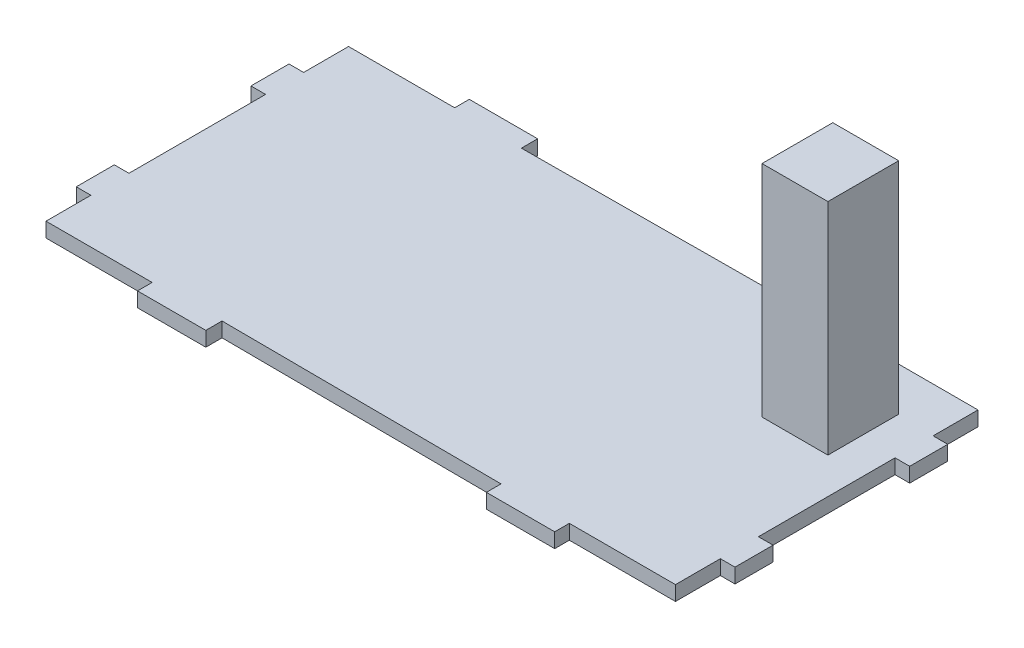
SolidWorks part; units mm, degrees
ref_plane "Front Plane" through (0, 0, 0) normal (0, 0, 1) x (1, 0, 0)
ref_plane "Top Plane" through (0, 0, 0) normal (0, 1, 0) x (1, 0, 0)
ref_plane "Right Plane" through (0, 0, 0) normal (1, 0, 0) x (0, 0, -1)
sketch "Sketch1" plane through (0, 0, 0) normal (0, 1, 0) x (1, 0, 0)
  line L1 (-67.5, 34) -> (67.5, 34)
  line L2 (-67.5, 34) -> (-67.5, -34)
  line L3 (-67.5, -34) -> (67.5, -34)
  line L4 (67.5, 34) -> (67.5, -34)
  line L5 (-67.5, 34) -> (67.5, -34) construction
  line L6 (-67.5, -34) -> (67.5, 34) construction
  point P0 (0, 0)
  dimension "D1" = 68
  dimension "D2" = 135
extrude "Boss-Extrude1" add sketch "Sketch1" along normal blind 3
sketch "Sketch2" plane through (0, 3, 0) normal (0, 1, 0) x (1, 0, 0)
  line L0 (-67.5, 34) -> (-64.5, 34)
  line L1 (67.5, 34) -> (-67.5, 34) construction
  line L2 (-64.5, 34) -> (-64.5, 21.8)
  line L3 (-64.5, 21.8) -> (-67.5, 21.8)
  line L4 (-67.5, 34) -> (-67.5, -34) construction
  line L5 (-67.5, 21.8) -> (-67.5, 14)
  line L6 (-67.5, 14) -> (-64.5, 14)
  line L7 (-64.5, 14) -> (-64.5, -14)
  line L8 (-64.5, -14) -> (-67.5, -14)
  line L9 (-67.5, -14) -> (-67.5, -21.8)
  line L10 (-67.5, -21.8) -> (-64.5, -21.8)
  line L11 (-64.5, -21.8) -> (-64.5, -34)
  line L12 (-67.5, -34) -> (67.5, -34) construction
  line L13 (-64.5, -34) -> (-67.5, -34)
  line L14 (-67.5, -34) -> (-67.5, -21.8)
  line L15 (-67.5, -14) -> (-67.5, 14)
  line L16 (-67.5, 21.8) -> (-67.5, 34)
  line M2 (67.5, 34) -> (-67.5, 34)
  line M3 (-67.5, 34) -> (-67.5, -34)
  line M4 (-67.5, -34) -> (67.5, -34)
  dimension "D1" = 3
  dimension "D2" = 12.2
  dimension "D3" = 7.8
  dimension "D4" = 28
  dimension "D5" = 7.8
  dimension "D6" = 12.2
extrude "Cut-Extrude1" cut sketch "Sketch2" against normal blind 3 contours L3 L2 M2 M3 | L8 L7 L6 M3 | L11 L10 M3 M4
mirror "Mirror1" about plane through (0, 0, 0) normal (1, 0, 0) of "Cut-Extrude1"
sketch "Sketch3" plane through (0, 3, 0) normal (0, 1, 0) x (1, 0, 0)
  line L0 (-64.5, 34) -> (-64.5, 31)
  line L1 (-64.5, 34) -> (-64.5, 21.8) construction
  line L2 (-64.5, 31) -> (-42.75, 31)
  line L3 (-42.75, 31) -> (-42.75, 34)
  line L4 (64.5, 34) -> (-64.5, 34) construction
  line L5 (-42.75, 34) -> (-28.75, 34)
  line L6 (-28.75, 34) -> (-28.75, 30.6714)
  line L7 (64.5, 34) -> (64.5, 31)
  line L8 (64.5, 34) -> (64.5, 21.8) construction
  line L9 (64.5, 31) -> (42.75, 31)
  line L10 (42.75, 31) -> (42.75, 34)
  line L11 (42.75, 34) -> (28.75, 34)
  line L12 (28.75, 34) -> (28.75, 31)
  line L13 (28.75, 31) -> (-28.75, 30.6714)
  line L14 (-64.5, 34) -> (-42.75, 34)
  line L15 (-28.75, 34) -> (28.75, 34)
  line L16 (42.75, 34) -> (64.5, 34)
  line M2 (64.5, 21.8) -> (64.5, 34)
  line M3 (64.5, 34) -> (-64.5, 34)
  line M4 (-64.5, 34) -> (-64.5, 21.8)
  dimension "D1" = 3
  dimension "D2" = 21.75
  dimension "D3" = 14
  dimension "D4" = 3
  dimension "D5" = 21.75
  dimension "D6" = 14
extrude "Cut-Extrude2" cut sketch "Sketch3" against normal blind 3 contours L2 L3 M3 M4 | L13 L12 L6 M3 | L10 L9 M2 M3
mirror "Mirror2" about plane through (0, 0, 0) normal (0, 0, 1) of "Cut-Extrude2"
sketch "Sketch4" plane through (0, 3, 0) normal (0, 1, 0) x (1, 0, 0)
  line L0 (67.5, 34) -> (50.39, 34)
  line L1 (50.39, 34) -> (50.39, 14.85)
  line L3 (43.64, 22.1) -> (57.14, 22.1)
  line L4 (43.64, 22.1) -> (43.64, 7.6)
  line L5 (43.64, 7.6) -> (57.14, 7.6)
  line L6 (57.14, 22.1) -> (57.14, 7.6)
  line L7 (43.64, 22.1) -> (57.14, 7.6) construction
  line L8 (43.64, 7.6) -> (57.14, 22.1) construction
  dimension "D1" = 17.11
  dimension "D2" = 19.15
  dimension "D3" = 14.5
  dimension "D4" = 13.5
extrude "Boss-Extrude2" add sketch "Sketch4" along normal blind 45
